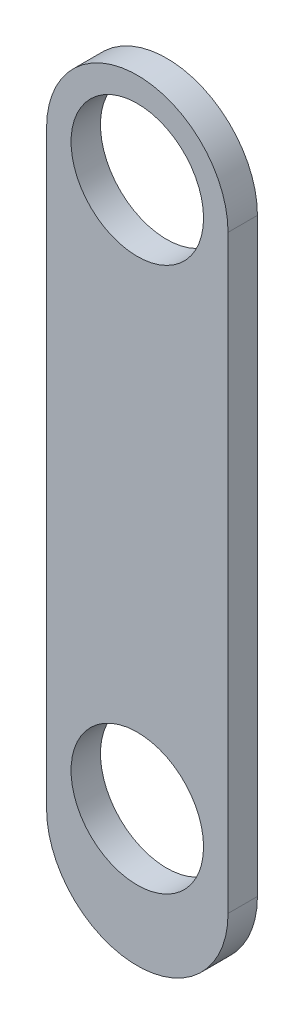
SolidWorks part; units mm, degrees
material "ASTM A36 Steel"
ref_plane "Front Plane" through (0, 0, 0) normal (0, 0, 1) x (1, 0, 0)
ref_plane "Top Plane" through (0, 0, 0) normal (0, 1, 0) x (1, 0, 0)
ref_plane "Right Plane" through (0, 0, 0) normal (1, 0, 0) x (0, 0, -1)
sketch "Sketch1" plane through (0, 0, 0) normal (0, 0, 1) x (1, 0, 0)
  line L2 (0, 0) -> (0, 82.55)
  line L4 (25.4, 0) -> (25.4, 82.55)
  arc A0 (25.4, 82.55) -> (0, 82.55) centre (12.7, 82.55) ccw
  circle A2 centre (12.7, 82.55) radius 9.271
  circle A3 centre (12.7, 6.35) radius 9.271
  arc A4 (0, 0) -> (25.4, 0) centre (12.7, 0) ccw
  point P9 (0, 0)
  dimension "D2" = 12.7
  dimension "D3" = 18.542
  dimension "D1" = 76.2
  dimension "D4" = 82.55
extrude "Boss-Extrude1" add sketch "Sketch1" along normal blind 4.1148
equation "\"Width\"=0.162"
equation "\"Link Diameter\"= 1"
equation "\"Link Radius\"= \"Link Diameter\" / 2"
equation "\"Length\"= 3"
equation "\"D1@Sketch1\"=\"Length\""
equation "\"D2@Sketch1\"=\"Link Radius\""
equation "\"D1@Boss-Extrude1\"=\"Width\""
equation "\"Bracket Diameter with tol\"= 0.73"
equation "\"D3@Sketch1\"=\"Bracket Diameter with tol\""
